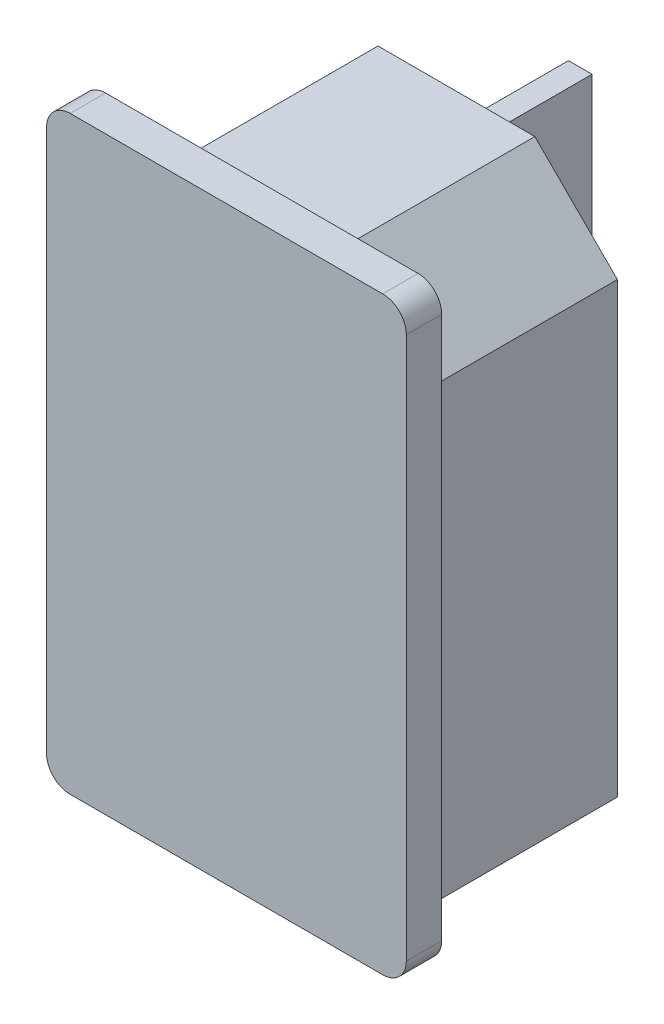
SolidWorks part; units mm, degrees
ref_plane "Front Plane" through (0, 0, 0) normal (0, 0, 1) x (1, 0, 0)
ref_plane "Top Plane" through (0, 0, 0) normal (0, 1, 0) x (1, 0, 0)
ref_plane "Right Plane" through (0, 0, 0) normal (1, 0, 0) x (0, 0, -1)
sketch "Sketch1" plane through (0, 0, 0) normal (0, 0, 1) x (1, 0, 0)
  line L0 (0, 25) -> (0, -25) construction
  line L1 (-13.25, 25) -> (13.25, 25)
  line L2 (-15.25, 23) -> (-15.25, -23)
  line L3 (-13.25, -25) -> (13.25, -25)
  line L4 (15.25, 23) -> (15.25, -23)
  arc A0 (13.25, 25) -> (15.25, 23) centre (13.25, 23) cw
  arc A1 (-15.25, -23) -> (-13.25, -25) centre (-13.25, -23) ccw
  arc A2 (13.25, -25) -> (15.25, -23) centre (13.25, -23) ccw
  arc A3 (-13.25, 25) -> (-15.25, 23) centre (-13.25, 23) ccw
  dimension "D1" = 2
  dimension "D2" = 30.5
  dimension "D3" = 50
extrude "Boss-Extrude1" add sketch "Sketch1" against normal blind 3
sketch "Sketch2" plane through (0, 0, -3) normal (0, 0, -1) x (-1, 0, 0)
  line L0 (-13.65, 16.5) -> (-6.65, 23.5)
  line L1 (-6.65, 23.5) -> (6.65, 23.5)
  line L2 (-13.65, 16.5) -> (-13.65, -23.5)
  line L3 (-13.65, -23.5) -> (13.65, -23.5)
  line L4 (13.65, 16.5) -> (13.65, -23.5)
  line L5 (13.65, 16.5) -> (6.65, 23.5)
  line L6 (0, 23.5) -> (0, -23.5) construction
  dimension "D1" = 47
  dimension "D2" = 27.3
  dimension "D3" = 7
extrude "Boss-Extrude2" add sketch "Sketch2" along normal blind 16.5
chamfer "Chamfer1" distance 2 angle 45 2 edges at (13.65, -23.5, -11.25) (-13.65, -23.5, -11.25)
sketch "Sketch4" plane through (0, 0, -19.5) normal (0, 0, -1) x (-1, 0, 0)
  line L0 (0, 20) -> (0, -20) construction
  line L1 (-1, 20) -> (1, 20)
  line L2 (-1, 20) -> (-1, -20)
  line L3 (-1, -20) -> (1, -20)
  line L4 (1, 20) -> (1, -20)
  dimension "D1" = 2
  dimension "D2" = 40
extrude "Boss-Extrude3" add sketch "Sketch4" along normal offset from surface (10.5 mm away) 30 up to face at (0, 0, 0)
